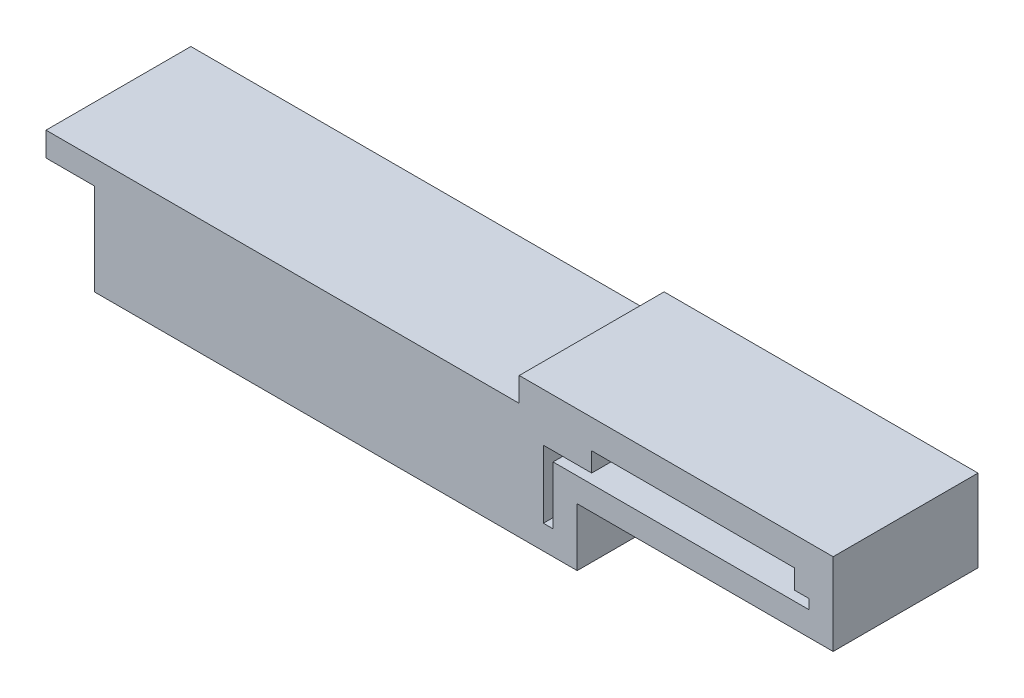
SolidWorks part; units mm, degrees
ref_plane "정면" through (0, 0, 0) normal (0, 0, 1) x (1, 0, 0)
ref_plane "윗면" through (0, 0, 0) normal (0, 1, 0) x (1, 0, 0)
ref_plane "우측면" through (0, 0, 0) normal (1, 0, 0) x (0, 0, -1)
sketch "스케치1" plane through (0, 0, 0) normal (0, 0, 1) x (1, 0, 0)
  line L18 (0, 0) -> (2, 0)
  line L19 (2, 0) -> (2, 12)
  line L20 (2, 12) -> (55, 12)
  line L21 (55, 12) -> (55, 14)
  line L22 (55, 14) -> (0, 14)
  line L23 (0, 14) -> (0, 0)
  line L24 (-5, -5) -> (7, -5)
  line L25 (7, -5) -> (7, 7)
  line L26 (7, 7) -> (60, 7)
  line L27 (60, 7) -> (60, 19)
  line L29 (-5, 19) -> (-5, -5)
  line L30 (52, 14) -> (52, 18)
  line L31 (52, 18) -> (10, 18)
  line L32 (10, 18) -> (10, 14)
  line L33 (-5, 19) -> (-5, 24)
  line L34 (60, 19) -> (-5, 19) construction
  line L35 (-5, 24) -> (60, 24)
  line L36 (60, 24) -> (60, 19)
  dimension "D1" = 2
  dimension "D2" = 2
  dimension "D3" = 14
  dimension "D4" = 55
  dimension "D6" = 45
  dimension "D7" = 3
  dimension "D8" = 4
  dimension "D9" = 5
  dimension "D5" = 5
extrude "보스-돌출2" add sketch "스케치1" along normal blind 30 contours L34 L36 L35 L33 | L27 L34 L29 L24 L25 L26 L32 L31 L30 L22 L21 L20 L19 L18 L23
sketch "스케치4" plane through (0, 0, 0) normal (0, 0, -1) x (-1, 0, 0)
  line L0 (5, -5) -> (5, 24) construction
  line L1 (5, 19) -> (93, 19)
  line L2 (5, 19) -> (5, -5)
  line L3 (5, -5) -> (93, -5)
  line L4 (93, 19) -> (93, -5)
  line L6 (93, 19) -> (103, 19)
  line L7 (93, 19) -> (93, 14)
  line L8 (93, 14) -> (103, 14)
  line L9 (103, 19) -> (103, 14)
  line M5 (5, -5) -> (5, 24)
  dimension "D1" = 88
  dimension "D2" = 24
  dimension "D3" = 5
  dimension "D4" = 10
extrude "보스-돌출4" add sketch "스케치4" against normal blind 30 contours L4 L1 L3 M5 | L9 L6 L4 L8
